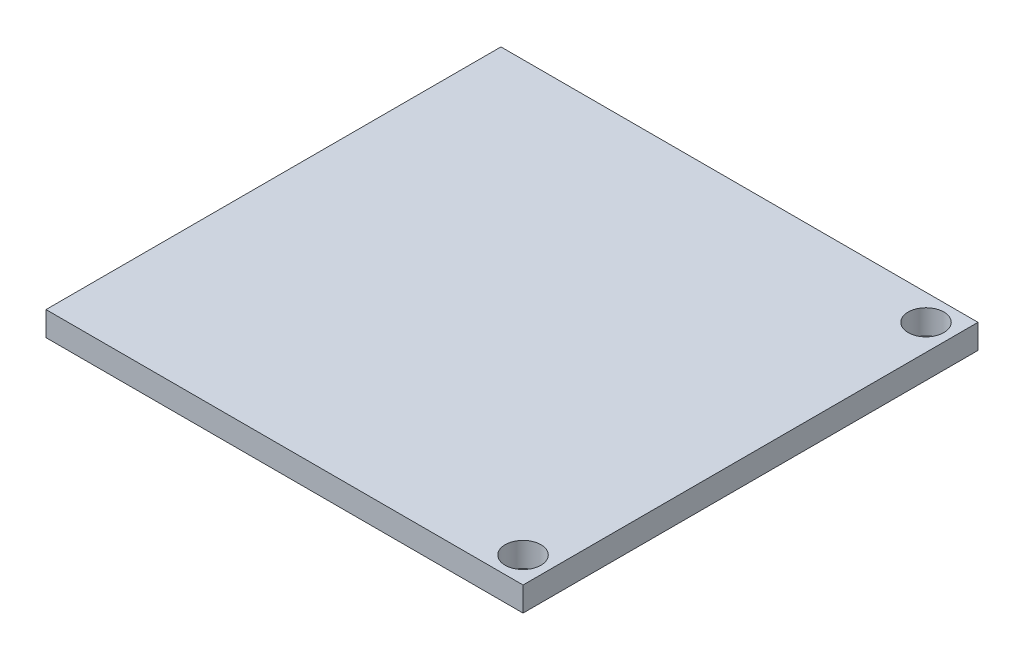
SolidWorks part; units mm, degrees
ref_plane "Front Plane" through (0, 0, 0) normal (0, 0, 1) x (1, 0, 0)
ref_plane "Top Plane" through (0, 0, 0) normal (0, 1, 0) x (1, 0, 0)
ref_plane "Right Plane" through (0, 0, 0) normal (1, 0, 0) x (0, 0, -1)
sketch "Sketch1" plane through (0, 0, 0) normal (0, 1, 0) x (1, 0, 0)
  line L0 (13.08, 14) -> (13.08, -14) construction
  line L1 (-14.68, 14) -> (14.68, 14)
  line L2 (-14.68, 14) -> (-14.68, -14)
  line L3 (-14.68, -14) -> (14.68, -14)
  line L4 (14.68, 14) -> (14.68, -14)
  line L5 (0, -14) -> (0, 14) construction
  line L6 (-14.68, 0) -> (14.68, 0) construction
  line L7 (-13.07, 14) -> (-13.07, -14) construction
  circle A0 centre (13.08, 12.4) radius 1.1
  circle A1 centre (13.08, -12.4) radius 1.1
  circle A2 centre (-13.07, 10.13) radius 1.1 construction
  circle A3 centre (-13.07, 7.59) radius 1.1 construction
  circle A4 centre (-13.07, 5.05) radius 1.1 construction
  circle A5 centre (-13.07, 2.51) radius 1.1 construction
  point P0 (0, 0)
  dimension "D4" = 2.2
  dimension "D5" = 1.6
  dimension "D6" = 1.6
  dimension "D8" = 16.51
  dimension "D9" = 2.2
  dimension "D10" = 2.54
  dimension "D11" = 2.54
  dimension "D12" = 2.54
  dimension "D1" = 28
  dimension "D2" = 29.36
  dimension "D3" = 1.6
  dimension "D7" = 1.61
extrude "Boss-Extrude1" add sketch "Sketch1" along normal blind 1.5
